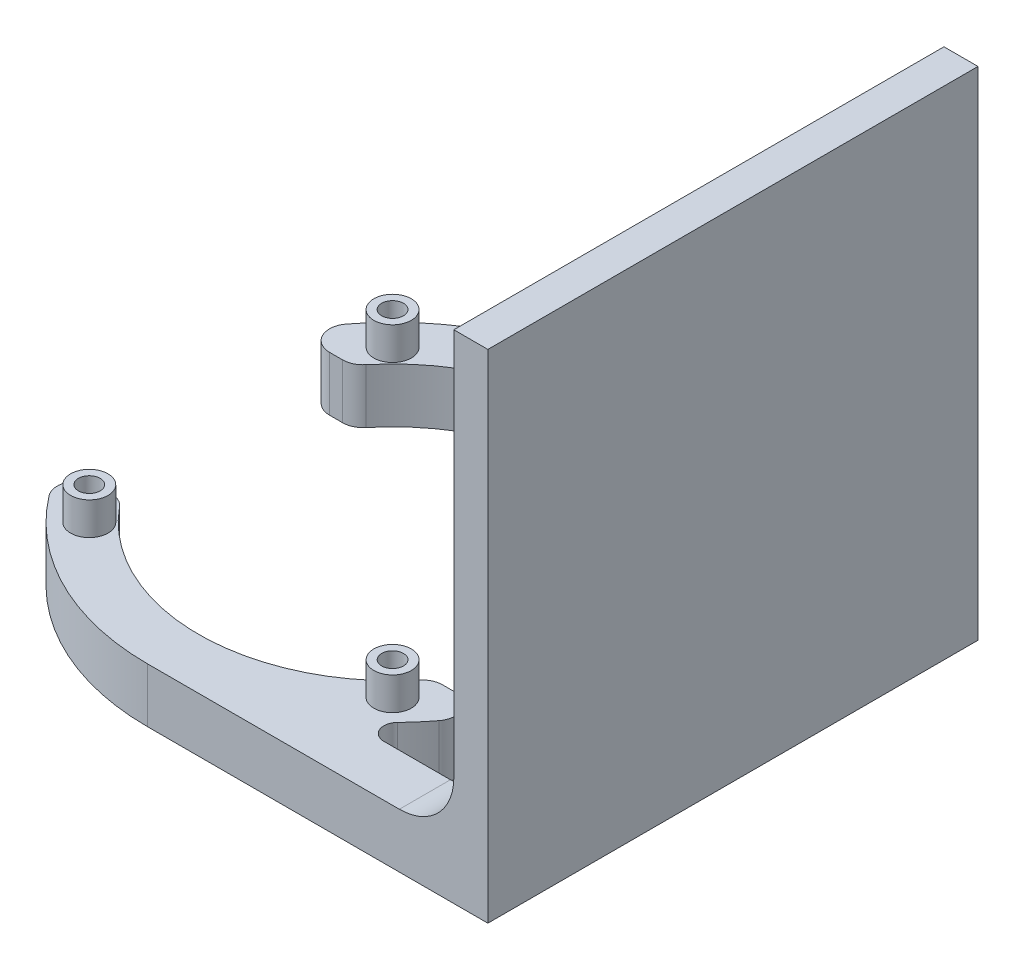
SolidWorks part; units mm, degrees
ref_plane "Front Plane" through (0, 0, 0) normal (0, 0, 1) x (1, 0, 0)
ref_plane "Top Plane" through (0, 0, 0) normal (0, 1, 0) x (1, 0, 0)
ref_plane "Right Plane" through (0, 0, 0) normal (1, 0, 0) x (0, 0, -1)
sketch "Sketch1" plane through (0, 0, 0) normal (0, 1, 0) x (1, 0, 0)
  line L1 (0, 36) -> (50, 36)
  line L3 (0, -36) -> (50, -36)
  line L4 (50, 36) -> (50, -36)
  line L5 (21.9943, 28.5) -> (45, 28.5)
  line L7 (21.9943, -28.5) -> (45, -28.5)
  line L8 (45, 28.5) -> (45, -28.5)
  arc A0 (0, 36) -> (0, -36) centre (0, 0) ccw
  circle A1 centre (0, 0) radius 28.5
  arc A2 (21.9943, -28.5) -> (21.9943, 28.5) centre (0, 0) ccw
  dimension "D1" = 72
  dimension "D3" = 57
  dimension "D2" = 50
  dimension "D4" = 5
extrude "Boss-Extrude2" add sketch "Sketch1" along normal blind 8
sketch "Sketch3" plane through (0, 8, 0) normal (0, 1, 0) x (1, 0, 0)
  line L0 (-17.4521, 0) -> (0, 0) construction
  line L1 (0, 0) -> (-22.2739, 22.2739) construction
  circle A0 centre (-22.2739, 22.2739) radius 2.75
  circle A1 centre (-22.2739, 22.2739) radius 1.6
  dimension "D3" = 5.5
  dimension "D4" = 3.2
  dimension "D1" = 45
  dimension "D2" = 31.5
extrude "Boss-Extrude3" add sketch "Sketch3" along normal blind 4.8
sketch "Sketch4" plane through (0, 8, 0) normal (0, 1, 0) x (1, 0, 0)
  line L0 (-18.2171, 0) -> (0, 0) construction
  line L1 (0, 0) -> (-22.2739, 22.2739) construction
  circle A0 centre (-22.2739, 22.2739) radius 1.6
  dimension "D2" = 3.2
  dimension "D1" = 45
  dimension "D3" = 31.5
extrude "Cut-Extrude1" cut sketch "Sketch4" against normal up to surface (8 mm away) up to face at (16, 0, 0)
sketch "Sketch5" plane through (0, 8, 0) normal (0, 1, 0) x (1, 0, 0)
  line L0 (0, -36) -> (50, -36) construction
  line L1 (50, 36) -> (45, 36)
  line L2 (50, 36) -> (50, -36)
  line L3 (50, -36) -> (45, -36)
  line L4 (45, 36) -> (45, -36)
  dimension "D1" = 5
extrude "Boss-Extrude4" add sketch "Sketch5" along normal blind 65
pattern_circular "CirPattern1" count 4 over 360 about axis through (0, 0, 0) along (0, 1, 0) of "Boss-Extrude3", "Cut-Extrude1"
sketch "Sketch7" plane through (0, 0, 0) normal (0, -1, 0) x (1, 0, 0)
  line L1 (-47.055, 17) -> (37.6341, 17)
  line L2 (-47.055, 17) -> (-47.055, -17)
  line L3 (-47.055, -17) -> (37.6341, -17)
  line L4 (37.6341, 17) -> (37.6341, -17)
  dimension "D1" = 17
  dimension "D2" = 34
extrude "Cut-Extrude2" cut sketch "Sketch7" against normal up to surface (8 mm away) up to face at (19.5239, 8, -22.2739)
fillet "Fillet2" radius 3 8 edges at (31.7333, 4, 17) (-22.8747, 4, 17) (22.8747, 4, 17) (31.7333, 4, -17) (-22.8747, 4, -17) (22.8747, 4, -17) (-31.7333, 4, -17) (-31.7333, 4, 17)
fillet "Fillet3" radius 2 2 edges at (21.9943, 4, -28.5) (21.9943, 4, 28.5)
fillet "Fillet4" radius 8 2 edges at (45, 8, -32.25) (45, 8, 32.25)
